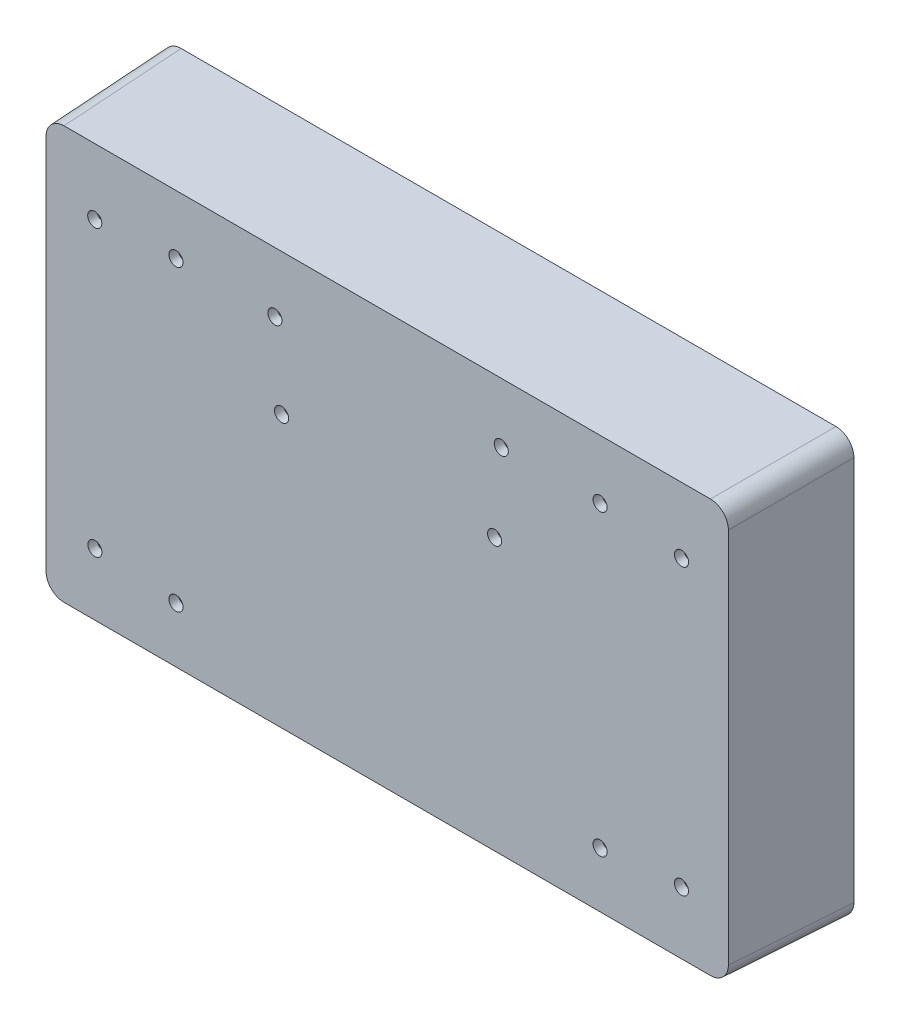
SolidWorks part; units mm, degrees
ref_plane "Спереди" through (0, 0, 0) normal (0, 0, 1) x (1, 0, 0)
ref_plane "Сверху" through (0, 0, 0) normal (0, 1, 0) x (1, 0, 0)
ref_plane "Справа" through (0, 0, 0) normal (1, 0, 0) x (0, 0, -1)
sketch "Эскиз1" plane through (0, 0, 0) normal (0, 0, 1) x (1, 0, 0)
  line L1 (33.9813, 62.4878) -> (-114.0187, 62.4878)
  line L2 (33.9813, 62.4878) -> (33.9813, -25.5122)
  line L3 (33.9813, -25.5122) -> (-114.0187, -25.5122)
  line L4 (-114.0187, 62.4878) -> (-114.0187, -25.5122)
  circle A0 centre (7.365, 51.2891) radius 1.5
  circle A1 centre (25.4913, 49.7762) radius 1.5
  circle A2 centre (25.4717, -13.6235) radius 1.5
  circle A3 centre (7.365, -15.128) radius 1.5
  circle A4 centre (-14.6336, 51.0787) radius 1.5
  circle A5 centre (-16.1162, 32.9981) radius 1.5
  circle A6 centre (-65.0189, 51.0787) radius 1.5
  circle A7 centre (-63.535, 32.9981) radius 1.5
  circle A8 centre (-87.0372, 51.2891) radius 1.5
  circle A9 centre (-105.1222, 49.7762) radius 1.5
  circle A10 centre (-87.0372, -15.128) radius 1.5
  circle A11 centre (-105.094, -13.6235) radius 1.5
  point P24 (33.9365, 62.0624)
  point P25 (33.9813, 62.4878)
  dimension "D1" = 3
  dimension "D2" = 3
  dimension "D3" = 3
  dimension "D4" = 3
  dimension "D5" = 3
  dimension "D6" = 3
  dimension "D7" = 3
  dimension "D8" = 3
  dimension "D9" = 3
  dimension "D10" = 3
  dimension "D11" = 3
  dimension "D12" = 3
  dimension "D13" = 148
  dimension "D14" = 88
extrude "Бобышка-Вытянуть1" add sketch "Эскиз1" against normal blind 25 draft 2 draft outward yes
fillet "Скругление1" radius 2 4 edges at (-114.4552, 62.9243, -12.5) (34.4178, 62.9243, -12.5) (34.4178, -25.9487, -12.5) (-114.4552, -25.9487, -12.5)
shell "Оболочка1" thickness 2
